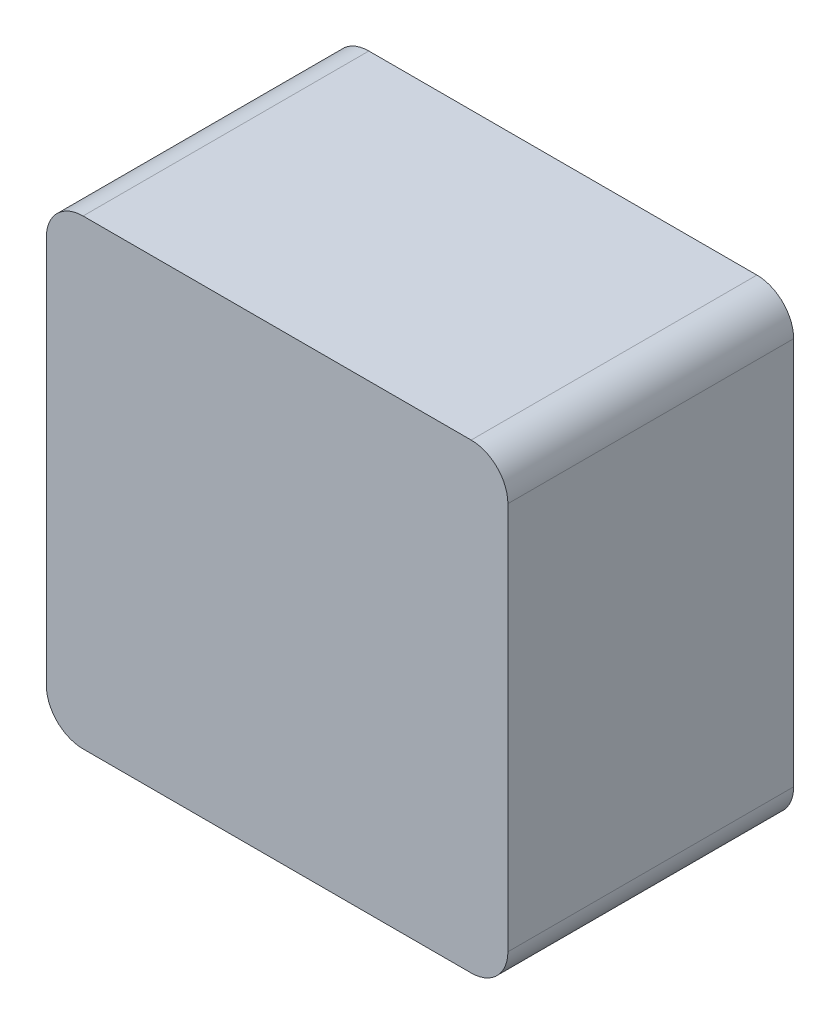
SolidWorks part; units mm, degrees
ref_plane "Front Plane" through (0, 0, 0) normal (0, 0, 1) x (1, 0, 0)
ref_plane "Top Plane" through (0, 0, 0) normal (0, 1, 0) x (1, 0, 0)
ref_plane "Right Plane" through (0, 0, 0) normal (1, 0, 0) x (0, 0, -1)
sketch "Basic Profile" plane through (0, 0, 0) normal (0, 0, 1) x (1, 0, 0)
  line L1 (-49.53, 49.53) -> (49.53, 49.53)
  line L2 (-49.53, 49.53) -> (-49.53, -49.53)
  line L3 (-49.53, -49.53) -> (49.53, -49.53)
  line L4 (49.53, 49.53) -> (49.53, -49.53)
  line L5 (-49.53, 49.53) -> (49.53, -49.53) construction
  line L6 (-49.53, -49.53) -> (49.53, 49.53) construction
  point P0 (0, 0)
  dimension "D1" = 99.06
sketch "Shell" plane through (0, 0, 0) normal (0, 0, 1) x (1, 0, 0)
  line L0 (-49.53, 49.53) -> (-49.53, -49.53) construction
  line L1 (-47.53, 52.53) -> (47.53, 52.53)
  line L2 (-52.53, 47.53) -> (-52.53, -47.53)
  line L3 (-47.53, -52.53) -> (47.53, -52.53)
  line L4 (52.53, 47.53) -> (52.53, -47.53)
  line L5 (-52.53, 52.53) -> (52.53, -52.53) construction
  line L6 (-52.53, -52.53) -> (52.53, 52.53) construction
  line L11 (-47.53, 56.53) -> (47.53, 56.53)
  line L12 (56.53, 47.53) -> (56.53, -47.53)
  line L13 (-47.53, -56.53) -> (47.53, -56.53)
  line L14 (-56.53, 47.53) -> (-56.53, -47.53)
  arc A0 (47.53, 52.53) -> (52.53, 47.53) centre (47.53, 47.53) cw
  arc A1 (47.53, -52.53) -> (52.53, -47.53) centre (47.53, -47.53) ccw
  arc A2 (-52.53, -47.53) -> (-47.53, -52.53) centre (-47.53, -47.53) ccw
  arc A3 (-47.53, 52.53) -> (-52.53, 47.53) centre (-47.53, 47.53) ccw
  arc A4 (47.53, 56.53) -> (56.53, 47.53) centre (47.53, 47.53) cw
  arc A5 (47.53, -56.53) -> (56.53, -47.53) centre (47.53, -47.53) ccw
  arc A6 (-56.53, -47.53) -> (-47.53, -56.53) centre (-47.53, -47.53) ccw
  arc A7 (-47.53, 56.53) -> (-56.53, 47.53) centre (-47.53, 47.53) ccw
  point P0 (0, 0)
  dimension "D3" = 5
  dimension "D1" = 3
  dimension "D2" = 4
extrude "Shell Walls" add sketch "Shell" along normal blind 68.58
sketch "Sketch3" plane through (0, 0, 68.58) normal (0, 0, 1) x (1, 0, 0)
  line L4 (-56.53, 47.53) -> (-56.53, -47.53)
  line L5 (-47.53, -56.53) -> (47.53, -56.53)
  line L6 (56.53, -47.53) -> (56.53, 47.53)
  line L7 (47.53, 56.53) -> (-47.53, 56.53)
  line L8 (-56.53, 47.53) -> (-56.53, -47.53)
  line L9 (-47.53, -56.53) -> (47.53, -56.53)
  line L10 (56.53, -47.53) -> (56.53, 47.53)
  line L11 (47.53, 56.53) -> (-47.53, 56.53)
  arc A4 (-47.53, 56.53) -> (-56.53, 47.53) centre (-47.53, 47.53) ccw
  arc A5 (-56.53, -47.53) -> (-47.53, -56.53) centre (-47.53, -47.53) ccw
  arc A6 (47.53, -56.53) -> (56.53, -47.53) centre (47.53, -47.53) ccw
  arc A7 (56.53, 47.53) -> (47.53, 56.53) centre (47.53, 47.53) ccw
  arc A8 (-47.53, 56.53) -> (-56.53, 47.53) centre (-47.53, 47.53) ccw
  arc A9 (-56.53, -47.53) -> (-47.53, -56.53) centre (-47.53, -47.53) ccw
  arc A10 (47.53, -56.53) -> (56.53, -47.53) centre (47.53, -47.53) ccw
  arc A11 (56.53, 47.53) -> (47.53, 56.53) centre (47.53, 47.53) ccw
  dimension "D1" = 0
extrude "Shell Top" add sketch "Sketch3" along normal blind 1.42
sketch "Rear-Cooling Fan Sketch" plane through (-56.53, 0, 0) normal (-1, 0, 0) x (0, 0, 1)
  line L0 (70, 47.53) -> (70, -47.53) construction
  line L1 (63, 46.03) -> (68, 46.03)
  line L2 (63, 46.03) -> (63, -46.03)
  line L3 (63, -46.03) -> (68, -46.03)
  line L4 (68, 46.03) -> (68, -46.03)
  line L5 (63, 46.03) -> (68, -46.03) construction
  line L6 (63, -46.03) -> (68, 46.03) construction
  line L7 (70, 47.53) -> (0, 47.53) construction
  point P0 (65.5, 0)
  dimension "D1" = 5
  dimension "D2" = 2
  dimension "D3" = 1.5
extrude "Rear-Cooling Fan Cutout" cut sketch "Rear-Cooling Fan Sketch" against normal up to next
